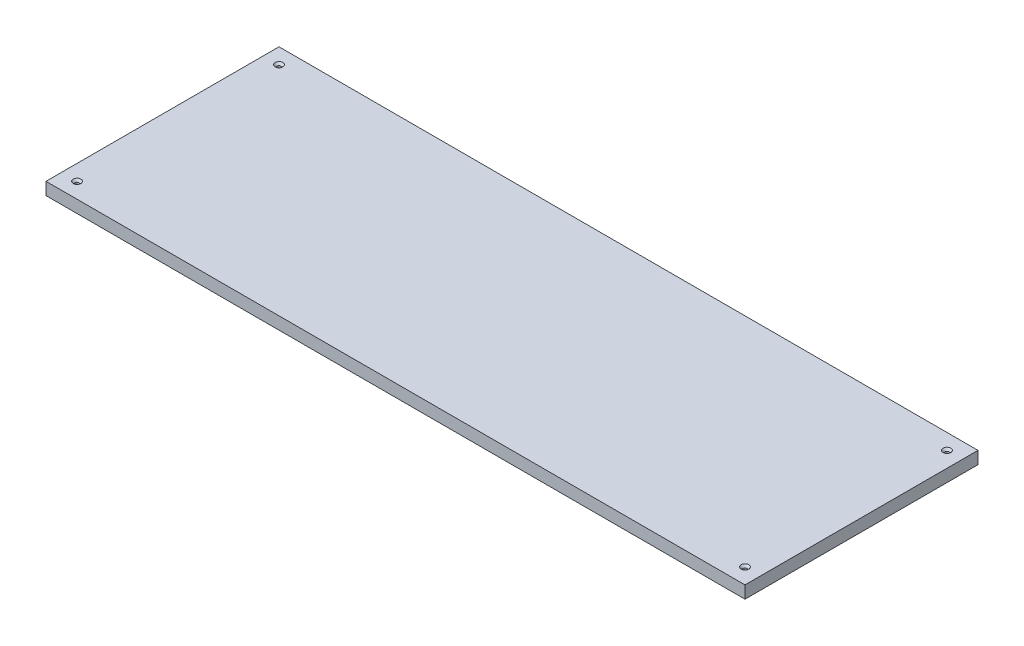
SolidWorks part; units mm, degrees
ref_plane "Спереди" through (0, 0, 0) normal (0, 0, 1) x (1, 0, 0)
ref_plane "Сверху" through (0, 0, 0) normal (0, 1, 0) x (1, 0, 0)
ref_plane "Справа" through (0, 0, 0) normal (1, 0, 0) x (0, 0, -1)
other "Configuration Table"
sketch "Эскиз2" plane through (0, 0, 0) normal (0, 1, 0) x (1, 0, 0)
  line L1 (-450, -150) -> (450, -150)
  line L2 (-450, -150) -> (-450, 150)
  line L3 (-450, 150) -> (450, 150)
  line L4 (450, -150) -> (450, 150)
  line L5 (-450, -150) -> (450, 150) construction
  line L6 (-450, 150) -> (450, -150) construction
  line L8 (0, -150) -> (0, 150) construction
  line L9 (-450, 0) -> (450, 0) construction
  point P0 (0, 0)
  point P10 (0, 0)
  point P15 (0, 0)
  point P20 (0, 0)
  dimension "D1" = 900
  dimension "D2" = 300
extrude "Бобышка-Вытянуть1" add sketch "Эскиз2" along normal blind 16
sketch "Эскиз7" plane through (0, 16, 0) normal (0, 1, 0) x (1, 0, 0)
  line L0 (-430, 150) -> (-430, -150) construction
  line L1 (450, 150) -> (-450, 150) construction
  line L2 (-450, -150) -> (450, -150) construction
  line L3 (-450, 130) -> (450, 130) construction
  line L4 (-450, 150) -> (-450, -150) construction
  line L5 (450, -150) -> (450, 150) construction
  point P12 (-430, 130)
  dimension "D1" = 20
  dimension "D2" = 20
hole_wizard "CSK для M4 винта с полупотайной головкой и крестообразным шлицем1" positions "Трехмерный эскиз2" profile "Эскиз8" countersink size "M4" standard "AS" end condition through all
sketch3d "Трехмерный эскиз2"
  point P0 (-430, 16, -130)
sketch "Эскиз8" plane through (-430, 16, -130) normal (1, 0, 0) x (0, 0, 1)
  line L0 (0, 0) -> (0, 16)
  line L1 (0, 16) -> (2.25, 16)
  line L2 (2.25, 16) -> (2.25, 2.6074)
  line L3 (2.25, 2.6074) -> (4.95, 0)
  line L5 (4.95, 0) -> (0, 0)
  line L6 (-2.25, 2.6074) -> (-4.95, 0) construction
  line L11 (0, -6.35) -> (0, 107.95) construction
  dimension "Диаметр сквозного отверстия" = 4.5
  dimension "Глубина сквозного отверстия" = 16
  dimension "Диаметр передней зенковки" = 9.9
  dimension "Угол передней зенковки" = 92
pattern_linear "Линейный массив1" count 2 spacing 860 along (1, 0, 0) count 2 spacing 260 along (0, 0, 1) of "CSK для M4 винта с полупотайной головкой и крестообразным шлицем1"
